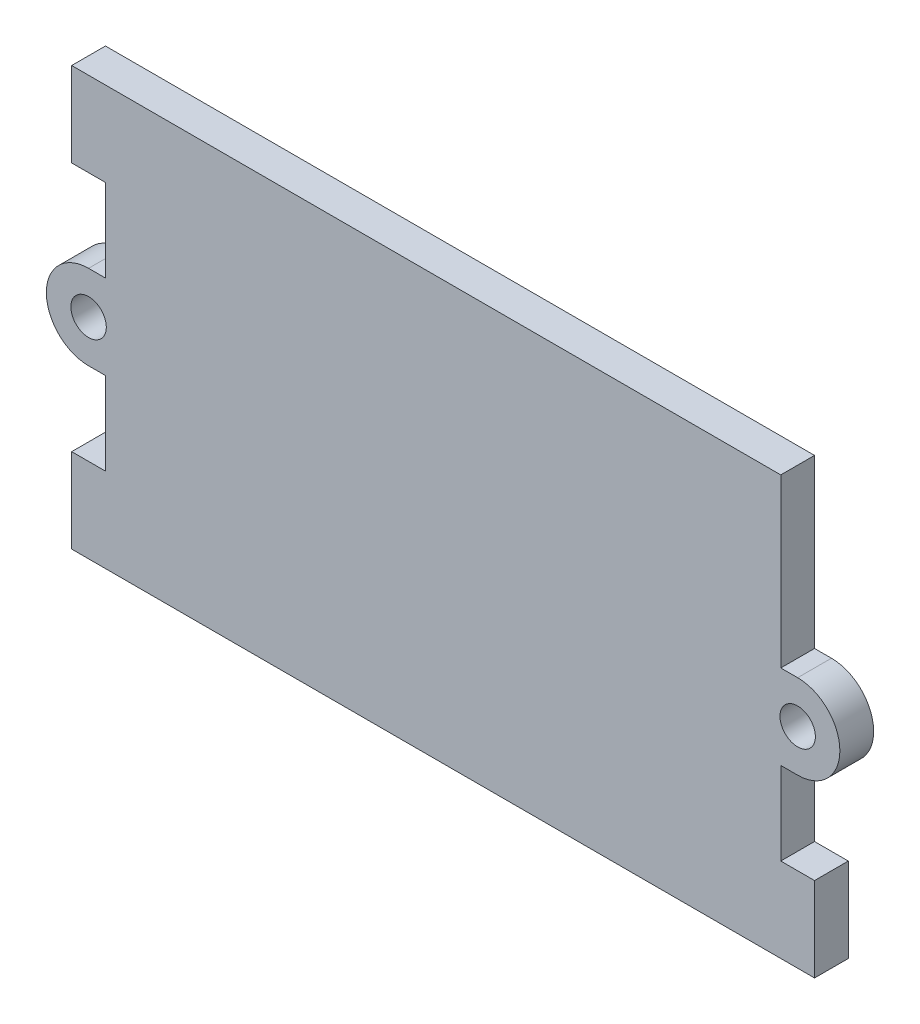
SolidWorks part; units mm, degrees
ref_plane "Plan de face" through (0, 0, 0) normal (0, 0, 1) x (1, 0, 0)
ref_plane "Plan de dessus" through (0, 0, 0) normal (0, 1, 0) x (1, 0, 0)
ref_plane "Plan de droite" through (0, 0, 0) normal (1, 0, 0) x (0, 0, -1)
sketch "Esquisse1" plane through (0, 0, 0) normal (0, 0, 1) x (1, 0, 0)
  line L0 (85, 49.6148) -> (80, 49.6148) construction
  line L1 (0, 0) -> (80, 0)
  line L2 (0, 0) -> (0, 49.6148)
  line L3 (0, 49.6148) -> (80, 49.6148)
  line L4 (80, 0) -> (80, 49.6148)
  dimension "D1" = 80
  dimension "D2" = 0
extrude "Boss.-Extru.1" add sketch "Esquisse1" along normal blind 4 contours L2 L3 L4 L1
sketch "Esquisse3" plane through (0, 0, 4) normal (0, 0, -1) x (-1, 0, 0)
  line L0 (-40, 0) -> (-40, 49.6148) construction
  line L1 (0, 0) -> (-80, 0) construction
  line L2 (0, 49.6148) -> (-80, 49.6148) construction
  line L4 (0, 0) -> (4, 0)
  line L5 (0, 0) -> (0, 10)
  line L6 (0, 10) -> (4, 10)
  line L7 (4, 0) -> (4, 10)
  line L8 (0, 24.8074) -> (-80, 24.8074) construction
  line L9 (0, 0) -> (0, 49.6148) construction
  line L10 (-80, 0) -> (-80, 49.6148) construction
  line L11 (0, 19.8074) -> (2, 19.8074)
  line L12 (0, 19.8074) -> (0, 29.8074)
  line L13 (0, 29.8074) -> (2, 29.8074)
  line L14 (4, 49.6148) -> (4, 39.6148)
  line L15 (0, 39.6148) -> (4, 39.6148)
  line L16 (0, 49.6148) -> (0, 39.6148)
  line L17 (0, 49.6148) -> (4, 49.6148)
  line L22 (-80, 29.8074) -> (-82, 29.8074)
  line L23 (-80, 19.8074) -> (-80, 29.8074)
  line L24 (-80, 19.8074) -> (-82, 19.8074)
  line L25 (-84, 0) -> (-84, 10)
  line L26 (-80, 10) -> (-84, 10)
  line L27 (-80, 0) -> (-80, 10)
  line L28 (-80, 0) -> (-84, 0)
  arc A0 (2, 19.8074) -> (2, 29.8074) centre (2, 24.8074) ccw
  arc A1 (-82, 19.8074) -> (-82, 29.8074) centre (-82, 24.8074) cw
  dimension "D1" = 5
  dimension "D4" = 4
  dimension "D2" = 2
  dimension "D3" = 10
extrude "Boss.-Extru.3" add sketch "Esquisse3" along normal blind 4
sketch "Esquisse4" plane through (0, 0, 0) normal (0, 0, -1) x (-1, 0, 0)
  circle A0 centre (2, 24.8074) radius 2.1
  circle A1 centre (-82, 24.8074) radius 2.1
  dimension "D1" = 4.2
  dimension "D2" = 4.2
extrude "Enlèv. mat.-Extru.1" cut sketch "Esquisse4" against normal through all
